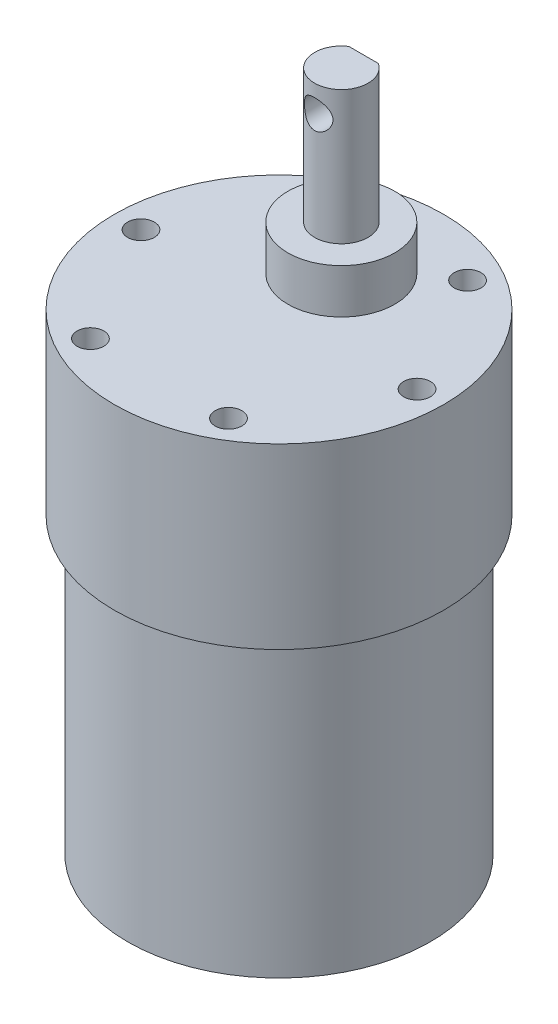
SolidWorks part; units mm, degrees
ref_plane "Front Plane" through (0, 0, 0) normal (0, 0, 1) x (1, 0, 0)
ref_plane "Top Plane" through (0, 0, 0) normal (0, 1, 0) x (1, 0, 0)
ref_plane "Right Plane" through (0, 0, 0) normal (1, 0, 0) x (0, 0, -1)
sketch "Sketch1" plane through (0, 0, 0) normal (0, 1, 0) x (1, 0, 0)
  circle A0 centre (0, 0) radius 17
  dimension "D1" = 34
extrude "Boss-Extrude1" add sketch "Sketch1" along normal blind 33
sketch "Sketch2" plane through (0, 33, 0) normal (0, 1, 0) x (1, 0, 0)
  circle A0 centre (0, 0) radius 18.5
  dimension "D1" = 37
extrude "Boss-Extrude2" add sketch "Sketch2" along normal blind 20
sketch "Sketch3" plane through (0, 53, 0) normal (0, 1, 0) x (1, 0, 0)
  line L0 (0, 0) -> (0, 7) construction
  circle A0 centre (0, 7) radius 6
  dimension "D2" = 12
  dimension "D1" = 7
extrude "Boss-Extrude3" add sketch "Sketch3" along normal blind 5
sketch "Sketch4" plane through (0, 58, 0) normal (0, 1, 0) x (1, 0, 0)
  circle A0 centre (0, 7) radius 3
  dimension "D1" = 6
extrude "Boss-Extrude4" add sketch "Sketch4" along normal blind 15
sketch "Sketch5" plane through (0, 73, 0) normal (0, 1, 0) x (1, 0, 0)
  line L0 (0, 7) -> (0, 5.1865) construction
  line L1 (-1.6583, 9.5) -> (1.6583, 9.5)
  arc A0 (-1.6583, 9.5) -> (1.6583, 9.5) centre (0, 7) ccw construction
  circle A1 centre (0, 7) radius 3 construction
  circle A2 centre (0, 7) radius 3 construction
  arc A3 (-1.6583, 9.5) -> (1.6583, 9.5) centre (0, 7) cw
  point P6 (0, 4)
  circle M4 centre (0, 7) radius 3
  dimension "D1" = 5.5
extrude "Cut-Extrude1" cut sketch "Sketch5" against normal blind 14 contours L1 M4
sketch "Sketch6" plane through (0, 53, 0) normal (0, 1, 0) x (1, 0, 0)
  line L0 (0, 0) -> (7.75, 13.4234) construction
  line L1 (0, 0) -> (15.5, 0) construction
  line L2 (0, 0) -> (7.75, -13.4234) construction
  line L3 (0, 0) -> (-7.75, -13.4234) construction
  line L4 (0, 0) -> (-15.5, 0) construction
  line L5 (0, 0) -> (-7.75, 13.4234) construction
  line L6 (0, 0) -> (0, -5.8355) construction
  circle A0 centre (15.5, 0) radius 1.5
  circle A1 centre (-15.5, 0) radius 1.5
  circle A2 centre (-7.75, -13.4234) radius 1.5
  circle A3 centre (7.75, -13.4234) radius 1.5
  circle A4 centre (-7.75, 13.4234) radius 1.5
  circle A5 centre (7.75, 13.4234) radius 1.5
  circle A6 centre (0, 0) radius 15.5 construction
  dimension "D1" = 31
  dimension "D4" = 3
  dimension "D2" = 60
  dimension "D3" = 60
extrude "Cut-Extrude2" cut sketch "Sketch6" against normal blind 10
sketch "Sketch7" plane through (0, 0, -9.5) normal (0, 0, -1) x (-1, 0, 0)
  line L0 (0, 70) -> (0, 73) construction
  line L1 (1.6583, 73) -> (-1.6583, 73) construction
  circle A0 centre (0, 70) radius 1.6
  dimension "D1" = 3.2
  dimension "D2" = 3
extrude "Cut-Extrude3" cut sketch "Sketch7" against normal blind 10
